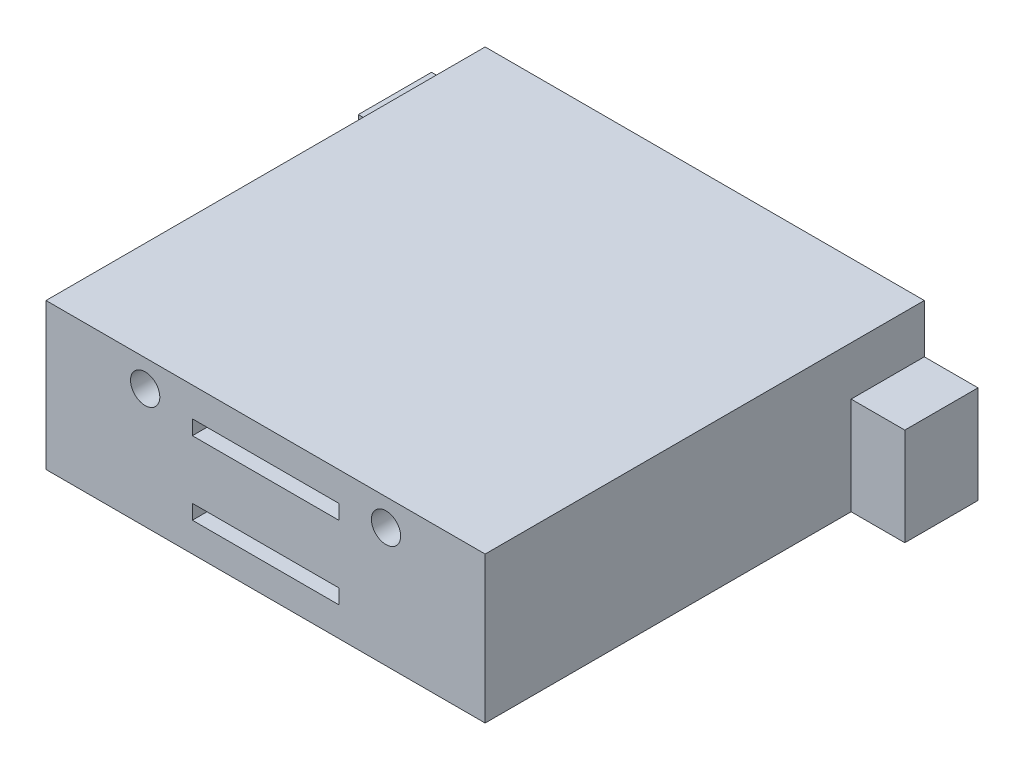
SolidWorks part; units mm, degrees
ref_plane "Front Plane" through (0, 0, 0) normal (0, 0, 1) x (1, 0, 0)
ref_plane "Top Plane" through (0, 0, 0) normal (0, 1, 0) x (1, 0, 0)
ref_plane "Right Plane" through (0, 0, 0) normal (1, 0, 0) x (0, 0, -1)
sketch "Sketch1" plane through (0, 0, 0) normal (0, 0, 1) x (1, 0, 0)
  line L1 (0, 0) -> (90, 0)
  line L2 (0, 0) -> (0, 30)
  line L3 (0, 30) -> (90, 30)
  line L4 (90, 0) -> (90, 30)
  dimension "D1" = 90
  dimension "D2" = 30
extrude "Boss-Extrude1" add sketch "Sketch1" along normal blind 90
sketch "Sketch2" plane through (0, 0, 0) normal (0, 0, -1) x (-1, 0, 0)
  line L0 (-90, 0) -> (-90, 30) construction
  line L1 (-87, 28) -> (-3, 28)
  line L2 (-87, 28) -> (-87, 24)
  line L3 (-87, 24) -> (-3, 24)
  line L4 (-3, 28) -> (-3, 24)
  line L5 (-90, 30) -> (0, 30) construction
  dimension "D1" = 84
  dimension "D2" = 3
  dimension "D3" = 2
  dimension "D4" = 4
extrude "Cut-Extrude1" cut sketch "Sketch2" against normal blind 85
sketch "Sketch3" plane through (0, 0, 0) normal (0, 0, -1) x (-1, 0, 0)
  line L0 (-87, 24) -> (-3, 24) construction
  line L1 (-82, 24) -> (-8, 24)
  line L2 (-82, 24) -> (-82, 21)
  line L3 (-82, 21) -> (-8, 21)
  line L4 (-8, 24) -> (-8, 21)
  line L5 (-3, 24) -> (-3, 28) construction
  dimension "D1" = 3
  dimension "D2" = 74
  dimension "D3" = 5
extrude "Cut-Extrude2" cut sketch "Sketch3" against normal blind 85
sketch "Sketch4" plane through (0, 0, 0) normal (0, 0, -1) x (-1, 0, 0)
  line L0 (0, 30) -> (0, 0) construction
  line L1 (-87, 21) -> (-3, 21)
  line L2 (-87, 21) -> (-87, 18)
  line L3 (-87, 18) -> (-3, 18)
  line L4 (-3, 21) -> (-3, 18)
  line L5 (-82, 21) -> (-8, 21) construction
  point P4 (-3, 19.5)
  dimension "D1" = 84
  dimension "D2" = 3
  dimension "D3" = 3
  dimension "D4" = 0
extrude "Cut-Extrude3" cut sketch "Sketch4" against normal blind 85
sketch "Sketch5" plane through (0, 0, 0) normal (0, 0, -1) x (-1, 0, 0)
  line L0 (-87, 18) -> (-3, 18) construction
  line L1 (-82, 18) -> (-8, 18)
  line L2 (-82, 18) -> (-82, 15)
  line L3 (-82, 15) -> (-8, 15)
  line L4 (-8, 18) -> (-8, 15)
  line L5 (-87, 21) -> (-87, 18) construction
  dimension "D1" = 74
  dimension "D2" = 5
  dimension "D3" = 3
extrude "Cut-Extrude4" cut sketch "Sketch5" against normal blind 85
sketch "Sketch7" plane through (0, 0, 0) normal (0, 0, -1) x (-1, 0, 0)
  line L0 (-87, 21) -> (-87, 18) construction
  line L1 (-87, 15) -> (-3, 15)
  line L2 (-87, 15) -> (-87, 11)
  line L3 (-87, 11) -> (-3, 11)
  line L4 (-3, 15) -> (-3, 11)
  line L5 (-82, 15) -> (-8, 15) construction
  dimension "D1" = 84
  dimension "D2" = 4
  dimension "D3" = 0
  dimension "D4" = 0
extrude "Cut-Extrude5" cut sketch "Sketch7" against normal blind 85
sketch "Sketch8" plane through (0, 0, 0) normal (0, 0, -1) x (-1, 0, 0)
  line L0 (-87, 11) -> (-3, 11) construction
  line L1 (-82, 11) -> (-8, 11)
  line L2 (-82, 11) -> (-82, 8)
  line L3 (-82, 8) -> (-8, 8)
  line L4 (-8, 11) -> (-8, 8)
  line L7 (-3, 11) -> (-3, 15) construction
  line L8 (-87, 15) -> (-87, 11) construction
  dimension "D1" = 74
  dimension "D2" = 5
  dimension "D3" = 5
  dimension "D4" = 3
extrude "Cut-Extrude6" cut sketch "Sketch8" against normal blind 85
sketch "Sketch9" plane through (0, 0, 0) normal (0, 0, -1) x (-1, 0, 0)
  line L0 (-82, 8) -> (-8, 8) construction
  line L1 (-87, 8) -> (-3, 8)
  line L2 (-87, 8) -> (-87, 5)
  line L3 (-87, 5) -> (-3, 5)
  line L4 (-3, 8) -> (-3, 5)
  line L5 (-90, 0) -> (-90, 30) construction
  dimension "D1" = 84
  dimension "D2" = 3
  dimension "D3" = 0
  dimension "D4" = 3
extrude "Cut-Extrude7" cut sketch "Sketch9" against normal blind 85
sketch "Sketch10" plane through (0, 0, 0) normal (0, 0, -1) x (-1, 0, 0)
  line L0 (-87, 5) -> (-3, 5) construction
  line L1 (-82, 5) -> (-8, 5)
  line L2 (-82, 5) -> (-82, 2)
  line L3 (-82, 2) -> (-8, 2)
  line L4 (-8, 5) -> (-8, 2)
  line L5 (-90, 0) -> (-90, 30) construction
  dimension "D1" = 74
  dimension "D2" = 3
  dimension "D3" = 8
extrude "Cut-Extrude8" cut sketch "Sketch10" against normal blind 85
sketch "Sketch11" plane through (0, 0, 85) normal (0, 0, -1) x (-1, 0, 0)
  line L0 (-3, 24) -> (-3, 28) construction
  line L2 (-82, 2) -> (-8, 2) construction
  circle A0 centre (-20.32, 24.51) radius 3
  dimension "D1" = 17.32
  dimension "D3" = 6
  dimension "D2" = 22.51
extrude "Cut-Extrude9" cut sketch "Sketch11" against normal blind 85
ref_plane "Plane1" through (45, 0, 0) normal (-1, 0, 0) x (0, 0, 1)
mirror "Mirror1" about plane through (45, 0, 0) normal (-1, 0, 0) of "Cut-Extrude9"
ref_plane "Plane2" through (0, 15, 0) normal (0, 1, 0) x (1, 0, 0)
sketch "Sketch12" plane through (0, 0, 85) normal (0, 0, -1) x (-1, 0, 0)
  line L0 (-3, 24) -> (-3, 28) construction
  line L1 (-60, 24) -> (-30, 24)
  line L2 (-60, 24) -> (-60, 21)
  line L3 (-60, 21) -> (-30, 21)
  line L4 (-30, 24) -> (-30, 21)
  line L5 (-3, 28) -> (-87, 28) construction
  dimension "D1" = 27
  dimension "D2" = 30
  dimension "D3" = 3
  dimension "D4" = 4
extrude "Cut-Extrude10" cut sketch "Sketch12" against normal blind 85
mirror "Mirror2" about plane through (0, 15, 0) normal (0, 1, 0) of "Cut-Extrude10"
sketch "Sketch13" plane through (0, 0, 0) normal (-1, 0, 0) x (0, 0, 1)
  line L1 (0, 0) -> (15, 0)
  line L2 (0, 0) -> (0, 20)
  line L3 (0, 20) -> (15, 20)
  line L4 (15, 0) -> (15, 20)
  dimension "D1" = 15
  dimension "D2" = 20
extrude "Boss-Extrude2" add sketch "Sketch13" along normal blind 11
mirror "Mirror3" about plane through (45, 0, 0) normal (-1, 0, 0) of "Boss-Extrude2"
sketch "Sketch14" plane through (0, 0, 0) normal (0, 0, -1) x (-1, 0, 0)
  line L0 (11, 20) -> (11, 0) construction
  line L1 (11, 20) -> (0, 20) construction
  circle A0 centre (4, 10) radius 5
  dimension "D1" = 10
  dimension "D2" = 7
  dimension "D3" = 10
extrude "Cut-Extrude11" cut sketch "Sketch14" against normal blind 10
mirror "Mirror4" about plane through (45, 0, 0) normal (-1, 0, 0) of "Cut-Extrude11"
